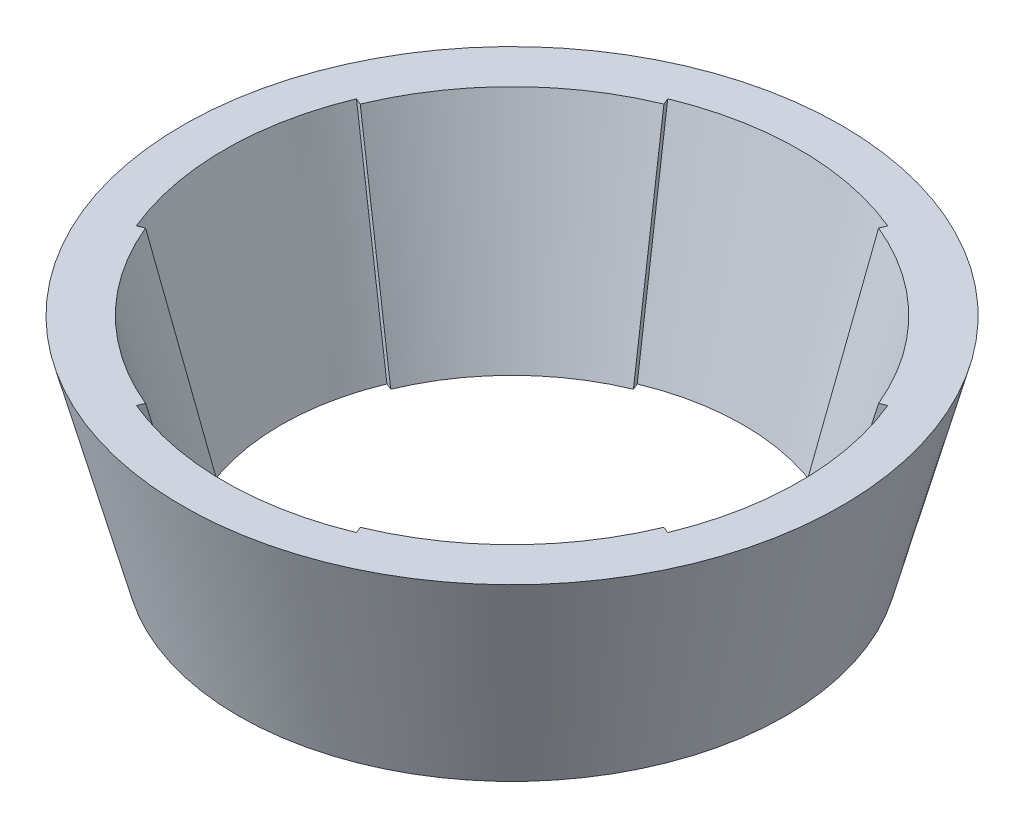
SolidWorks part; units mm, degrees
material "Ceramic Porcelain"
ref_plane "Front Plane" through (0, 0, 0) normal (0, 0, 1) x (1, 0, 0)
ref_plane "Top Plane" through (0, 0, 0) normal (0, 1, 0) x (1, 0, 0)
ref_plane "Right Plane" through (0, 0, 0) normal (1, 0, 0) x (0, 0, -1)
sketch "Sketch1" plane through (0, 0, 0) normal (0, 0, 1) x (1, 0, 0)
  line L0 (40.64, 0) -> (50.8489, 38.1)
  line L1 (50.8489, 38.1) -> (59.7389, 38.1)
  line L2 (59.7389, 38.1) -> (49.53, 0)
  line L3 (49.53, 0) -> (40.64, 0)
  line L4 (0, 0) -> (0, 52.1855) construction
  dimension "D1" = 40.64
  dimension "D2" = 8.89
  dimension "D3" = 38.1
  dimension "D4" = 105
revolve "Revolve1" add sketch "Sketch1" angle 360 about L4
sketch "Sketch2" plane through (0, 0, 0) normal (0, 0, 1) x (1, 0, 0)
  line L0 (50.8489, 38.1) -> (40.64, 0)
  line L1 (40.64, 0) -> (41.91, 0)
  line L2 (-49.53, 0) -> (49.53, 0) construction
  line L3 (41.91, 0) -> (52.1189, 38.1)
  line L4 (59.7389, 38.1) -> (-59.7389, 38.1) construction
  line L5 (52.1189, 38.1) -> (50.8489, 38.1)
  line L6 (0, 0) -> (0, 49.3059) construction
  dimension "D1" = 1.27
revolve "Cut-Revolve1" cut sketch "Sketch2" angle 45 mid plane about L6
pattern_circular "CirPattern1" count 4 over 360 about axis through (0, 38.1, 0) along (0, -1, 0) of "Cut-Revolve1"
